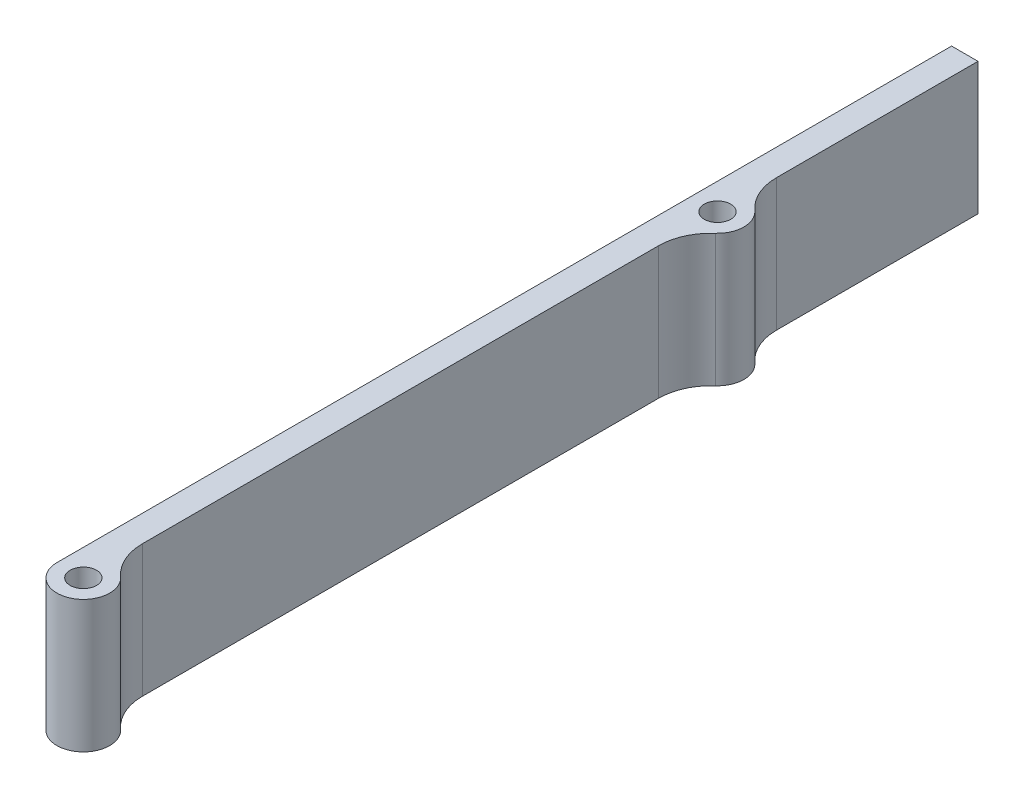
SolidWorks part; units mm, degrees
material "6061 Alloy"
ref_plane "Front Plane" through (0, 0, 0) normal (0, 0, 1) x (1, 0, 0)
ref_plane "Top Plane" through (0, 0, 0) normal (0, 1, 0) x (1, 0, 0)
ref_plane "Right Plane" through (0, 0, 0) normal (1, 0, 0) x (0, 0, -1)
sketch "Sketch2" plane through (0, 0, 0) normal (0, 1, 0) x (1, 0, 0)
  line L0 (0, 33.8476) -> (0, -135.4524)
  line L1 (0, -135.4524) -> (5, -135.4524) construction
  line L2 (0, 33.8476) -> (5, 33.8476)
  line L3 (5, 33.8476) -> (5, -135.4524) construction
  line L4 (5, 33.8476) -> (5, -4.2721)
  line L5 (5, -26.6328) -> (5, -124.2721)
  arc A0 (0, -135.4524) -> (8.3333, -131.7257) centre (5, -135.4524) ccw
  circle A1 centre (5, -15.4524) radius 5 construction
  circle A2 centre (5, -15.4524) radius 2.5
  circle A3 centre (5, -135.4524) radius 2.5
  arc A4 (8.3333, -11.7257) -> (8.3333, -19.1792) centre (5, -15.4524) cw
  arc A5 (5, -124.2721) -> (8.3333, -131.7257) centre (15, -124.2721) ccw
  arc A6 (5, -26.6328) -> (8.3333, -19.1792) centre (15, -26.6328) cw
  arc A7 (5, -4.2721) -> (8.3333, -11.7257) centre (15, -4.2721) ccw
  point P13 (5, -130.4524)
  dimension "D1" = 169.3
  dimension "D2" = 10
  dimension "D3" = 5
  dimension "D4" = 10
  dimension "D5" = 5
  dimension "D6" = 5
  dimension "D7" = 120
extrude "Boss-Extrude1" add sketch "Sketch2" along normal blind 25
sketch "Sketch3" plane through (0, 0, -33.8476) normal (0, 0, -1) x (-1, 0, 0)
  line L0 (-2.5, 0) -> (-2.5, 10) construction
  line L1 (-2.5, 10) -> (-2.5, 20) construction
  circle A0 centre (-2.5, 10) radius 1
  circle A1 centre (-2.5, 20) radius 1
  dimension "D1" = 10
  dimension "D2" = 10
extrude "Cut-Extrude1" cut sketch "Sketch3" against normal blind 25
